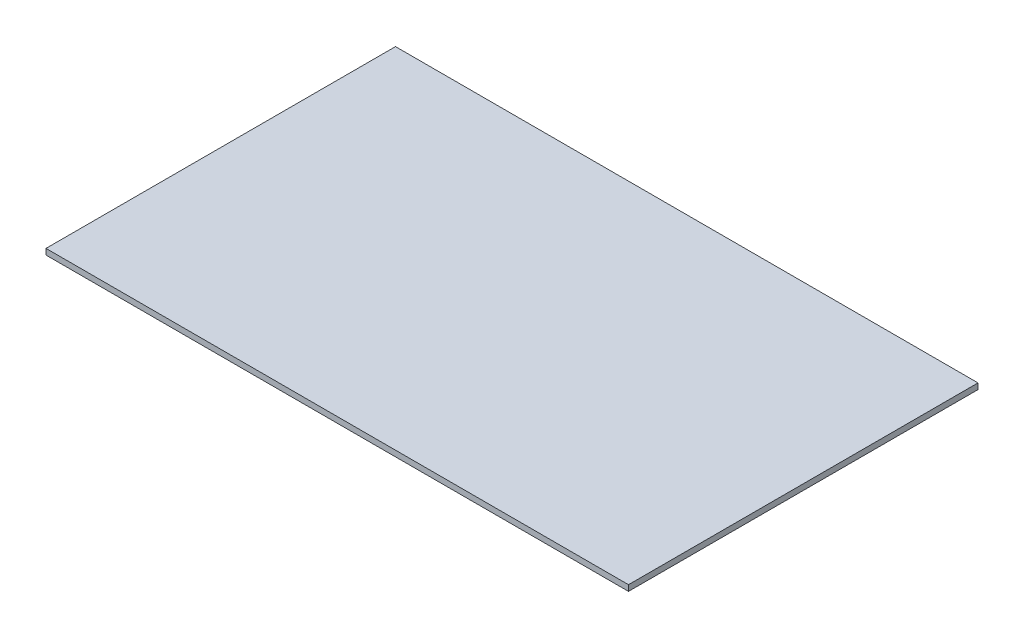
SolidWorks part; units mm, degrees
ref_plane "Alzado" through (0, 0, 0) normal (0, 0, 1) x (1, 0, 0)
ref_plane "Planta" through (0, 0, 0) normal (0, 1, 0) x (1, 0, 0)
ref_plane "Vista lateral" through (0, 0, 0) normal (1, 0, 0) x (0, 0, -1)
sketch "Croquis1" plane through (0, 0, 0) normal (0, 1, 0) x (1, 0, 0)
  line L1 (250, -150) -> (-250, -150)
  line L2 (250, -150) -> (250, 150)
  line L3 (250, 150) -> (-250, 150)
  line L4 (-250, -150) -> (-250, 150)
  line L5 (250, -150) -> (-250, 150) construction
  line L6 (250, 150) -> (-250, -150) construction
  point P0 (0, 0)
  dimension "D1" = 300
  dimension "D2" = 500
extrude "Saliente-Extruir1" add sketch "Croquis1" along normal blind 5
